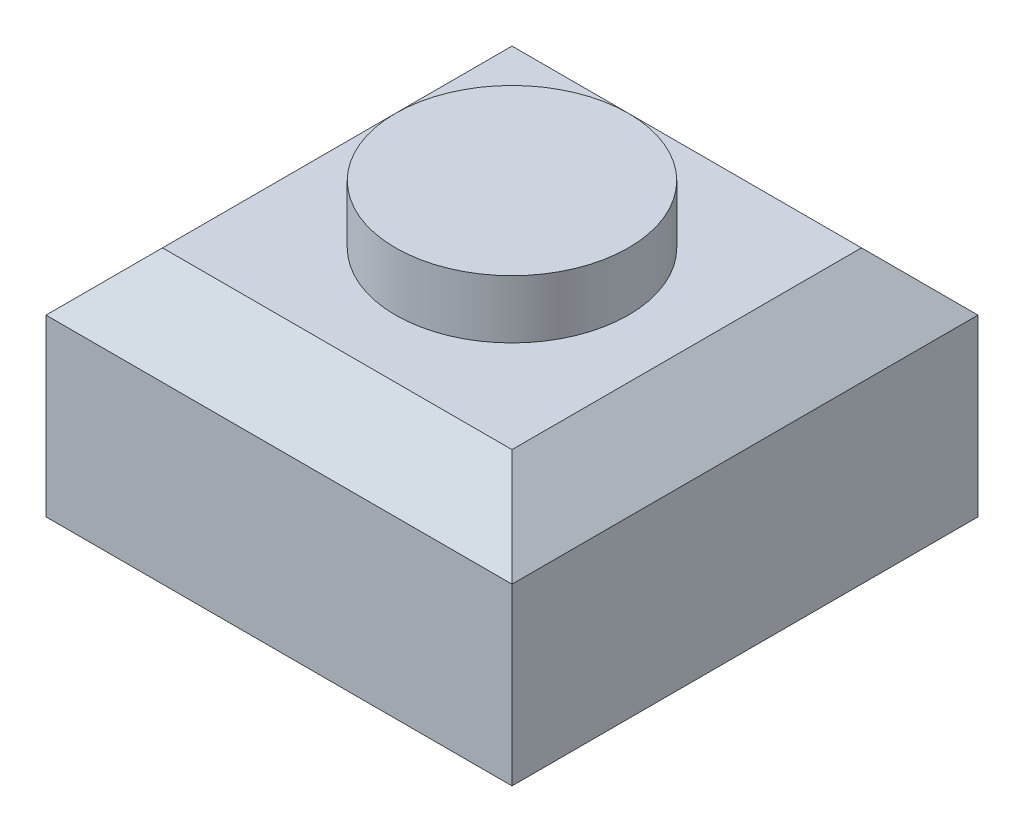
SolidWorks part; units mm, degrees
ref_plane "Front Plane" through (0, 0, 0) normal (0, 0, 1) x (1, 0, 0)
ref_plane "Top Plane" through (0, 0, 0) normal (0, 1, 0) x (1, 0, 0)
ref_plane "Right Plane" through (0, 0, 0) normal (1, 0, 0) x (0, 0, -1)
sketch "Sketch4" plane through (0, 0, 0) normal (0, 1, 0) x (1, 0, 0)
  line L1 (-40, 40) -> (40, 40)
  line L2 (-40, 40) -> (-40, -40)
  line L3 (-40, -40) -> (40, -40)
  line L4 (40, 40) -> (40, -40)
  dimension "D1" = 40
  dimension "D2" = 40
  dimension "D3" = 80
  dimension "D4" = 80
extrude "Boss-Extrude1" add sketch "Sketch4" along normal blind 40
sketch "Sketch5" plane through (0, 40, 0) normal (0, 1, 0) x (1, 0, 0)
  circle A0 centre (0, 0) radius 20
extrude "Boss-Extrude2" add sketch "Sketch5" along normal blind 10
chamfer "Chamfer1" distance 10 angle 45 4 edges at (0, 40, -40) (40, 40, 0) (0, 40, 40) (-40, 40, 0)
